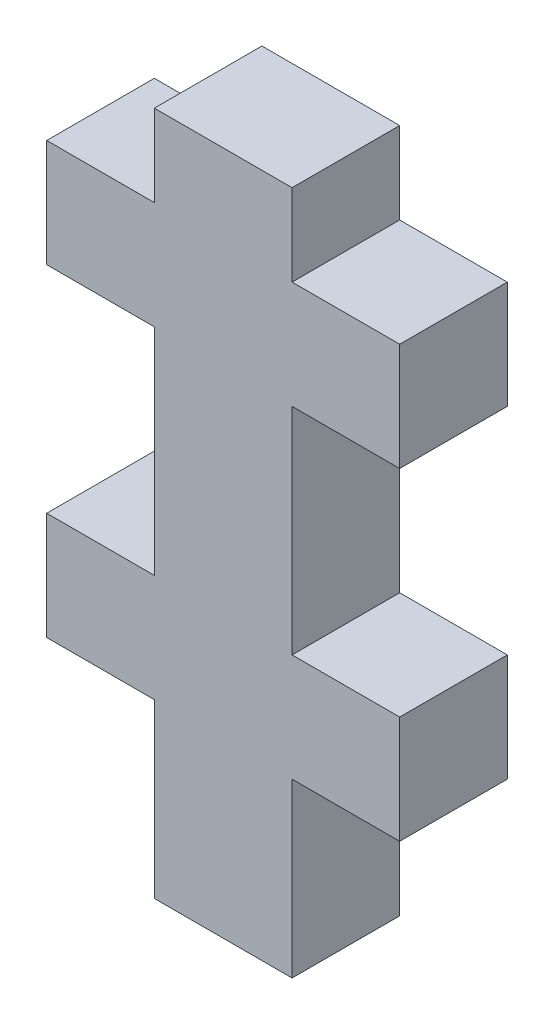
SolidWorks part; units mm, degrees
ref_plane "Front Plane" through (0, 0, 0) normal (0, 0, 1) x (1, 0, 0)
ref_plane "Top Plane" through (0, 0, 0) normal (0, 1, 0) x (1, 0, 0)
ref_plane "Right Plane" through (0, 0, 0) normal (1, 0, 0) x (0, 0, -1)
sketch "Sketch1" plane through (0, 0, 0) normal (0, 0, 1) x (1, 0, 0)
  line L0 (0, 18) -> (11.2208, 18) construction
  line L1 (0, 0) -> (6.4, 0)
  line L2 (0, 0) -> (0, 31.8) construction
  line L3 (0, 31.8) -> (6.4, 31.8)
  line L4 (6.4, 0) -> (6.4, 31.8) construction
  line L5 (0, 13) -> (0, 23)
  line L6 (-5, 23) -> (-5, 28)
  line L7 (-5, 28) -> (0, 28)
  line L8 (-5, 23) -> (0, 23)
  line L10 (0, 13) -> (-5, 13)
  line L11 (-5, 13) -> (-5, 8)
  line L12 (-5, 8) -> (0, 8)
  line L13 (6.4, 18) -> (-4.8208, 18) construction
  line L14 (6.4, 23) -> (6.4, 13)
  line L15 (11.4, 13) -> (11.4, 8)
  line L16 (11.4, 8) -> (6.4, 8)
  line L17 (11.4, 13) -> (6.4, 13)
  line L19 (6.4, 23) -> (11.4, 23)
  line L20 (11.4, 23) -> (11.4, 28)
  line L21 (11.4, 28) -> (6.4, 28)
  line L22 (0, 31.8) -> (0, 28)
  line L23 (0, 8) -> (0, 0)
  line L24 (6.4, 0) -> (6.4, 8)
  line L25 (6.4, 28) -> (6.4, 31.8)
  dimension "D1" = 6.4
  dimension "D2" = 18
  dimension "D3" = 10
  dimension "D4" = 5
  dimension "D5" = 5
  dimension "D6" = 10
  dimension "D7" = 5
  dimension "D8" = 5
  dimension "D9" = 13.8
extrude "Boss-Extrude1" add sketch "Sketch1" along normal blind 5
